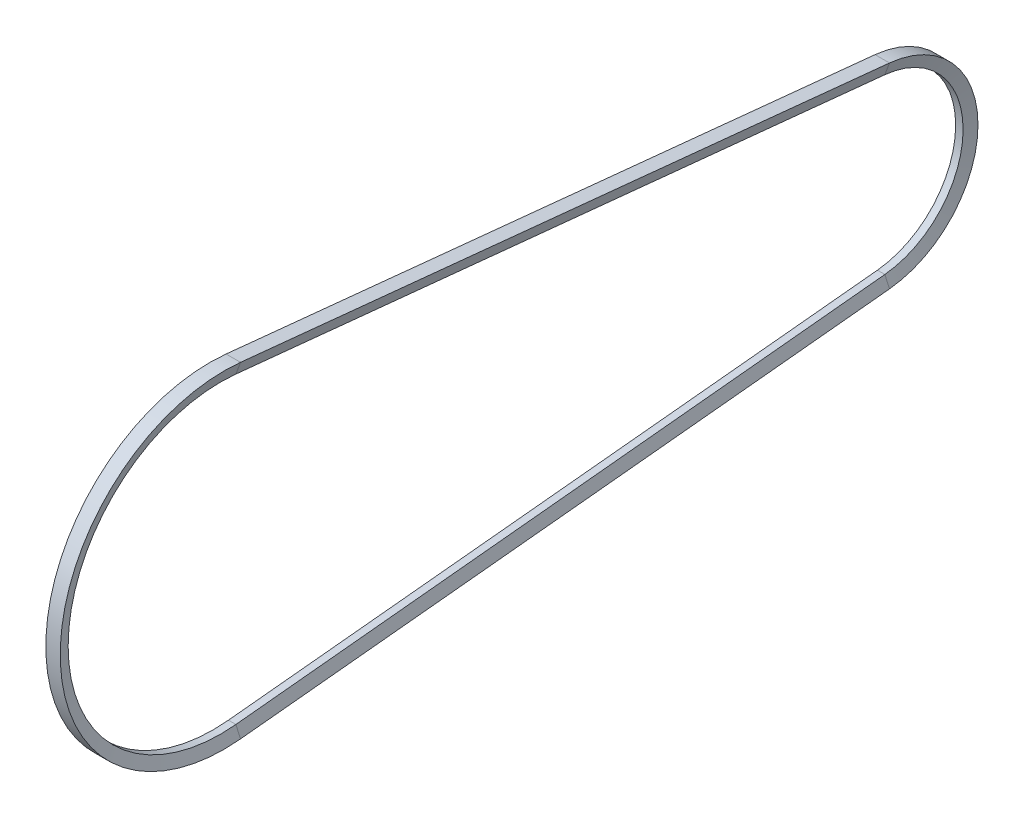
SolidWorks part; units mm, degrees
ref_plane "前视基准面" through (0, 0, 0) normal (0, 0, 1) x (1, 0, 0)
ref_plane "上视基准面" through (0, 0, 0) normal (0, 1, 0) x (1, 0, 0)
ref_plane "右视基准面" through (0, 0, 0) normal (1, 0, 0) x (0, 0, -1)
sketch "草图1" plane through (0, 0, 0) normal (1, 0, 0) x (0, 0, -1)
  line L0 (12.5, 124.3734) -> (507.5, 74.6241)
  line L1 (12.5, -124.3734) -> (507.5, -74.6241)
  line L2 (0, 0) -> (500, 0) construction
  arc A0 (12.5, 124.3734) -> (12.5, -124.3734) centre (0, 0) ccw
  arc A1 (507.5, -74.6241) -> (507.5, 74.6241) centre (500, 0) ccw
  dimension "D1" = 125
  dimension "D2" = 75
  dimension "D3" = 500
sketch "草图2" plane through (0, 0, 0) normal (0, 0, 1) x (1, 0, 0)
  line L0 (-5.5, 125) -> (5.5, 125)
  line L1 (5.5, 125) -> (2.8401, 116.3)
  line L2 (2.8401, 116.3) -> (-2.8401, 116.3)
  line L3 (-2.8401, 116.3) -> (-5.5, 125)
  line L4 (0, 116.3) -> (0, 125) construction
  line L5 (0, -125) -> (0, 125) construction
  dimension "D1" = 11
  dimension "D2" = 8.7
  dimension "D3" = 34
sweep "扫描1" add profiles "草图2" path "草图1"
equation "\"D3@草图1\" = \"D1@距离1@辐板轮_椭圆辐轮.Assembly\""
equation "\"D1@草图2\" = \"bd@草图1@大带轮_椭圆辐轮.Part\" "
equation "\"D2@草图2\" = \"hf@草图1@大带轮_椭圆辐轮.Part\" "
equation "\"D3@草图2\" = \"槽轮角@草图1@大带轮_椭圆辐轮.Part\" "
equation " \"D2@草图1\" = \"dd@草图1@小带轮_辐板轮.Part\"/2"
equation "\"D1@草图1\" = \"dd@草图1@大带轮_椭圆辐轮.Part\" /2"
